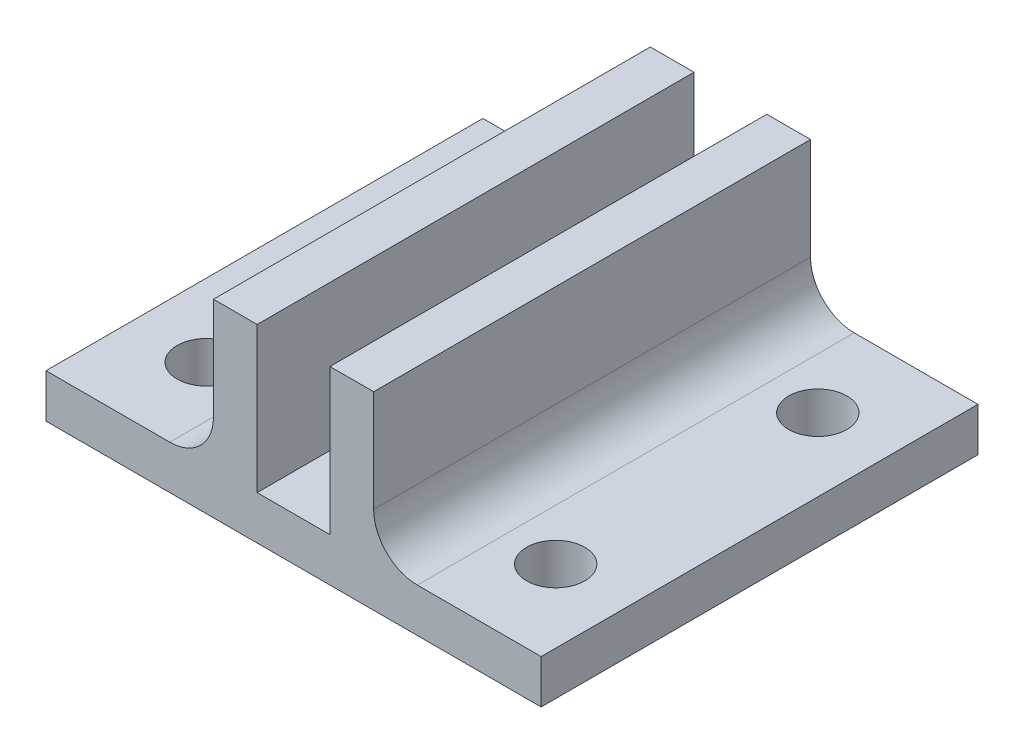
SolidWorks part; units mm, degrees
ref_plane "Front Plane" through (0, 0, 0) normal (0, 0, 1) x (1, 0, 0)
ref_plane "Top Plane" through (0, 0, 0) normal (0, 1, 0) x (1, 0, 0)
ref_plane "Right Plane" through (0, 0, 0) normal (1, 0, 0) x (0, 0, -1)
sketch "Sketch1" plane through (-298.9537, 67.3536, 0) normal (0, 0, 1) x (1, 0, 0)
  line L0 (318.4537, -54.3536) -> (318.4537, -64.3536)
  line L2 (310.4537, -64.3536) -> (310.4537, -54.3536)
  line L4 (321.4537, -64.3536) -> (321.4537, -54.3536)
  line L5 (318.4537, -64.3536) -> (313.4537, -64.3536)
  line L6 (313.4537, -64.3536) -> (313.4537, -54.3536)
  line L9 (310.4537, -64.3536) -> (298.9537, -64.3536)
  line L10 (298.9537, -64.3536) -> (298.9537, -67.3536)
  line L11 (298.9537, -67.3536) -> (332.9537, -67.3536)
  line L12 (332.9537, -67.3536) -> (332.9537, -64.3536)
  line L13 (332.9537, -64.3536) -> (321.4537, -64.3536)
  line L14 (310.4537, -54.3536) -> (313.4537, -54.3536)
  line L15 (318.4537, -54.3536) -> (321.4537, -54.3536)
  point P6 (12.839, 72.4288)
  dimension "D1" = 34
  dimension "D2" = 3
  dimension "D3" = 5
  dimension "D4" = 3
  dimension "D6" = 10
extrude "Boss-Extrude1" add sketch "Sketch1" along normal blind 30
sketch "Sketch2" plane through (0, 3, 0) normal (0, 1, 0) x (1, 0, 0)
  line L0 (29, -6) -> (29, 0) construction
  line L2 (29, -24) -> (29, -30) construction
  line L3 (34, -30) -> (22.5, -30) construction
  line L4 (34, 0) -> (22.5, 0) construction
  line L5 (34, -6) -> (29, -6) construction
  line L6 (34, -30) -> (34, 0) construction
  line L7 (29, -6) -> (5, -6) construction
  line L8 (5, -6) -> (0, -6) construction
  line L9 (0, -30) -> (0, 0) construction
  circle A0 centre (29, -6) radius 2
  circle A1 centre (29, -24) radius 2
  dimension "D1" = 4
  dimension "D2" = 24
  dimension "D3" = 18
extrude "Cut-Extrude1" cut sketch "Sketch2" against normal up to surface (3 mm away) up to face at (17, 0, 15)
ref_plane "Plane1" through (17, 0, 0) normal (1, 0, 0) x (0, 0, -1)
mirror "Mirror1" about plane through (17, 0, 0) normal (1, 0, 0) of "Cut-Extrude1"
fillet "Fillet1" radius 3 2 edges at (11.5, 3, 15) (22.5, 3, 15)
